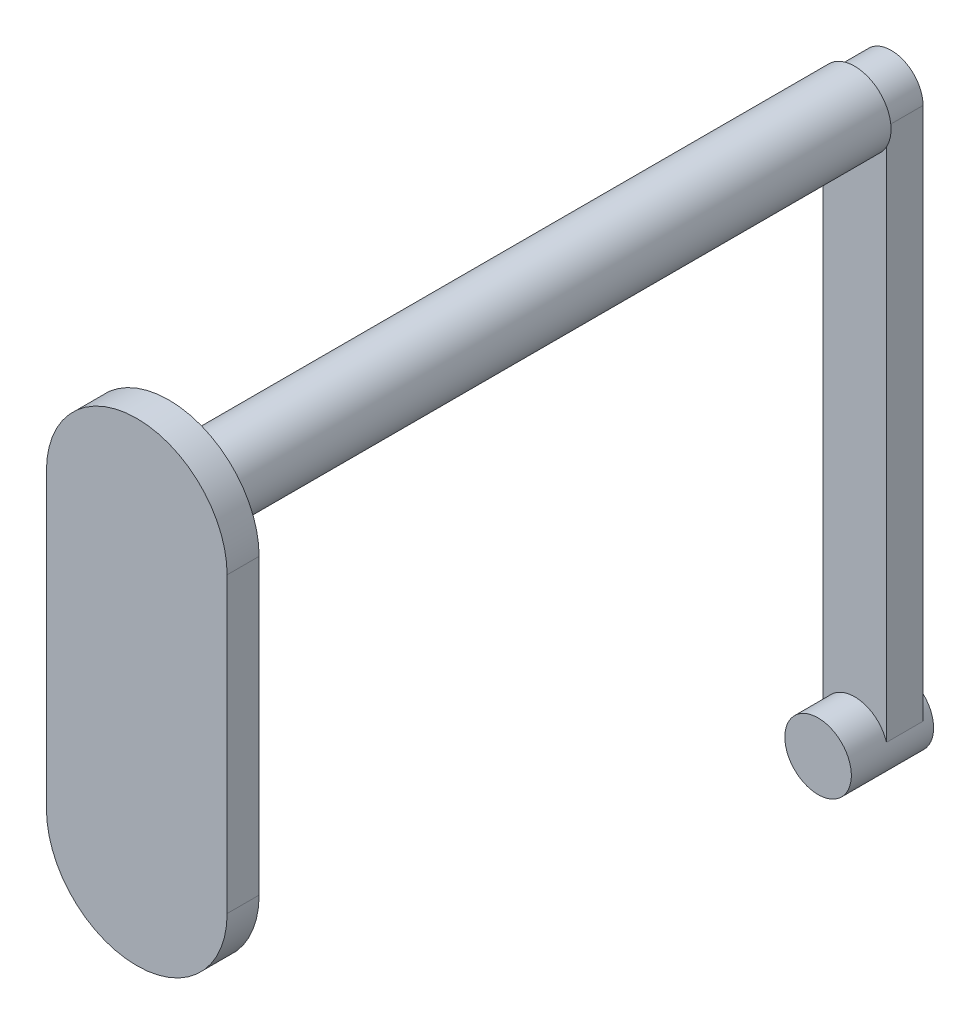
SolidWorks part; units mm, degrees
ref_plane "前视基准面" through (0, 0, 0) normal (0, 0, 1) x (1, 0, 0)
ref_plane "上视基准面" through (0, 0, 0) normal (0, 1, 0) x (1, 0, 0)
ref_plane "右视基准面" through (0, 0, 0) normal (1, 0, 0) x (0, 0, -1)
other "Configuration Table"
sketch "草图1" plane through (0, 0, 0) normal (0, 0, 1) x (1, 0, 0)
  line L0 (0, 0) -> (0, 85.2817) construction
  line L1 (0, 54.5865) -> (0, 118.7434) construction
  line L2 (-19.7578, 54.5865) -> (-19.7578, 118.7434)
  line L3 (19.7578, 54.5865) -> (19.7578, 118.7434)
  line L4 (-18.2126, 75.3193) -> (-75.1797, -18.7804) construction
  arc A0 (-19.7578, 54.5865) -> (19.7578, 54.5865) centre (0, 54.5865) ccw
  arc A1 (19.7578, 118.7434) -> (-19.7578, 118.7434) centre (0, 118.7434) ccw
  point P5 (0, 86.665)
extrude "凸台-拉伸1" add sketch "草图1" against normal blind 7
sketch "草图3" plane through (0, 0, -7) normal (0, 0, -1) x (-1, 0, 0)
  circle A0 centre (0, 118.7434) radius 7.951
extrude "凸台-拉伸2" add sketch "草图3" along normal blind 150
sketch "草图4" plane through (0, 0, -157) normal (0, 0, -1) x (-1, 0, 0)
  line L0 (0, 118.7434) -> (0, 0) construction
  line L1 (6.9587, 118.7434) -> (6.9587, 0)
  line L2 (-6.9587, 118.7434) -> (-6.9587, 0)
  arc A0 (6.9587, 118.7434) -> (-6.9587, 118.7434) centre (0, 118.7434) ccw
  arc A1 (-6.9587, 0) -> (6.9587, 0) centre (0, 0) ccw
  point P4 (0, 59.3717)
extrude "凸台-拉伸3" add sketch "草图4" along normal blind 8
sketch "草图5" plane through (0, 0, -165) normal (0, 0, -1) x (-1, 0, 0)
  circle A0 centre (0, 0) radius 7.2706
extrude "凸台-拉伸4" add sketch "草图5" along normal blind 2 and the other way blind 16
